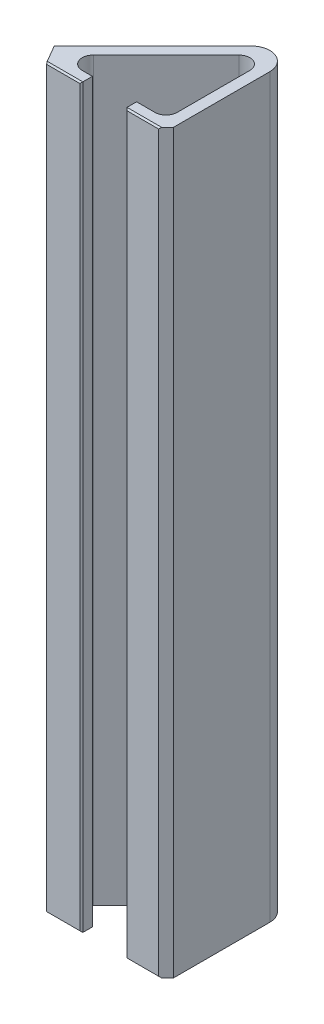
SolidWorks part; units mm, degrees
ref_plane "前视基准面" through (0, 0, 0) normal (0, 0, 1) x (1, 0, 0)
ref_plane "上视基准面" through (0, 0, 0) normal (0, 1, 0) x (1, 0, 0)
ref_plane "右视基准面" through (0, 0, 0) normal (1, 0, 0) x (0, 0, -1)
other "Configuration Table"
sketch "草图1" plane through (0, 0, 0) normal (0, 1, 0) x (1, 0, 0)
  line L0 (0, 0) -> (0, 30)
  line L1 (0, 30) -> (-30, 0)
  line L2 (-30, 0) -> (-20, 0)
  line L3 (3, 37.2426) -> (-37.2426, -3)
  line L4 (-37.2426, -3) -> (-20, -3)
  line L5 (3, -3) -> (3, 37.2426)
  line L6 (-20, 0) -> (-20, -3)
  line L7 (-8, 0) -> (-8, -3)
  line L8 (-8, -3) -> (3, -3)
  line L9 (-8, 0) -> (0, 0)
  line L10 (-37.2426, -3) -> (3, -3) construction
  line L12 (-30, 0) -> (0, 0) construction
  dimension "D1" = 30
  dimension "D2" = 30
  dimension "D4" = 12
  dimension "D5" = 8
  dimension "D3" = 3
extrude "凸台-拉伸1" add sketch "草图1" along normal blind 200
fillet "圆角1" radius 3 3 edges at (0, 100, 0) (-30, 100, 0) (0, 100, -30)
fillet "圆角2" radius 5 1 edges at (3, 100, -37.2426)
chamfer "倒角1" distance 7 angle 75 1 edges at (-37.2426, 100, 3)
chamfer "倒角2" distance 2 angle 45 1 edges at (3, 100, 3)
chamfer "倒角3" distance 0.4 angle 45 6 edges at (-3.5, 0, 3) (-3.5, 200, 3) (-8, 100, 3) (-24.7176, 0, 3) (-24.7176, 200, 3) (-20, 100, 3)
